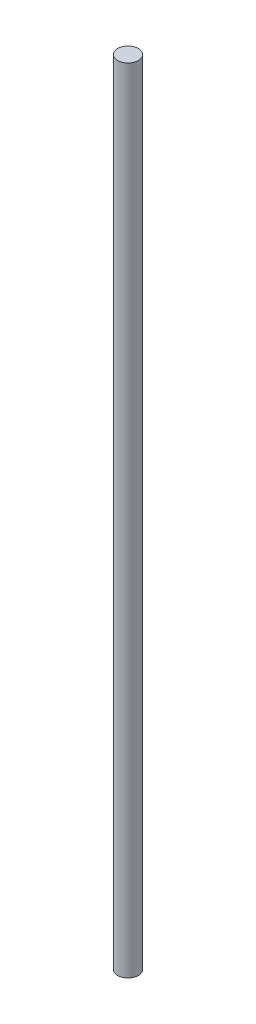
SolidWorks part; units mm, degrees
material "1060 Alloy"
ref_plane "Front Plane" through (0, 0, 0) normal (0, 0, 1) x (1, 0, 0)
ref_plane "Top Plane" through (0, 0, 0) normal (0, 1, 0) x (1, 0, 0)
ref_plane "Right Plane" through (0, 0, 0) normal (1, 0, 0) x (0, 0, -1)
sketch "Sketch1" plane through (0, 0, 0) normal (0, 1, 0) x (1, 0, 0)
  circle A0 centre (0, 0) radius 6
  dimension "D1" = 12
extrude "Boss-Extrude1" add sketch "Sketch1" along normal blind 457
